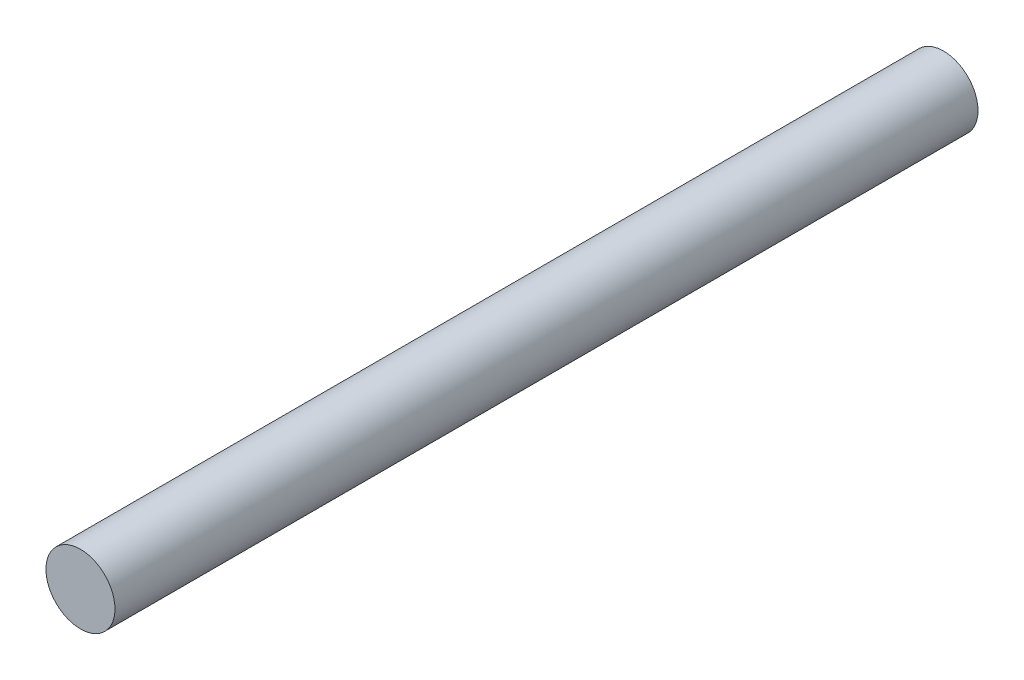
SolidWorks part; units mm, degrees
ref_plane "Plan de face" through (0, 0, 0) normal (0, 0, 1) x (1, 0, 0)
ref_plane "Plan de dessus" through (0, 0, 0) normal (0, 1, 0) x (1, 0, 0)
ref_plane "Plan de droite" through (0, 0, 0) normal (1, 0, 0) x (0, 0, -1)
sketch "Esquisse1" plane through (0, 0, 0) normal (0, 0, 1) x (1, 0, 0)
  circle A0 centre (0, 0) radius 20
  dimension "D1" = 40
extrude "Boss.-Extru.1" add sketch "Esquisse1" along normal blind 500
